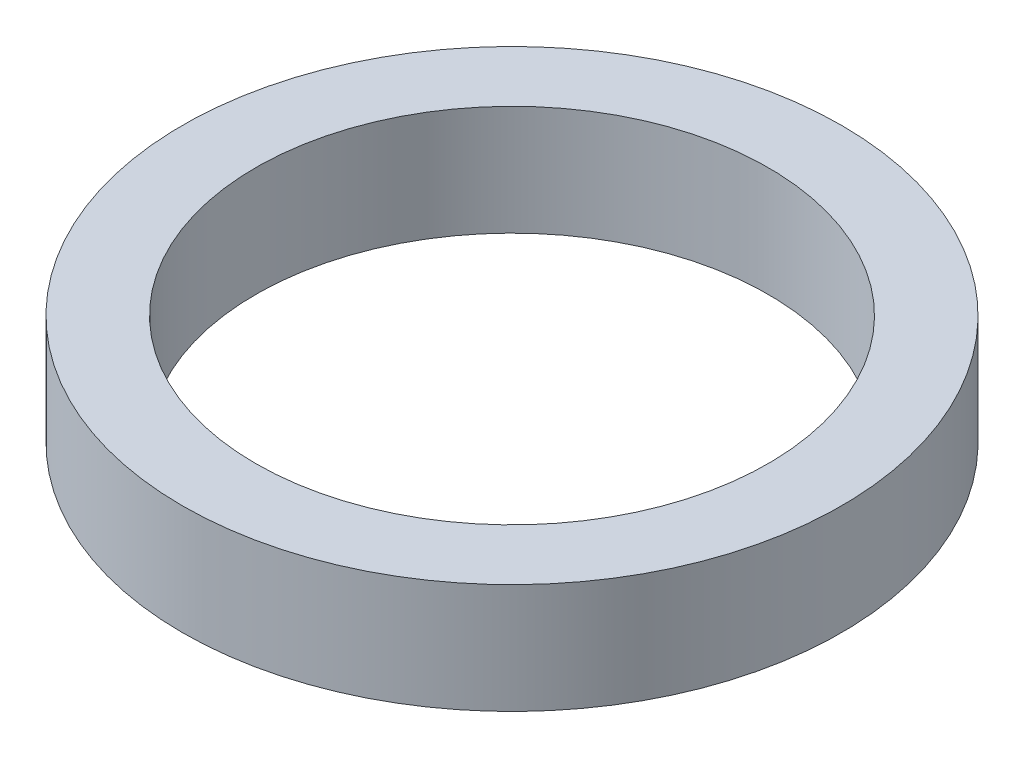
SolidWorks part; units mm, degrees
ref_plane "Front Plane" through (0, 0, 0) normal (0, 0, 1) x (1, 0, 0)
ref_plane "Top Plane" through (0, 0, 0) normal (0, 1, 0) x (1, 0, 0)
ref_plane "Right Plane" through (0, 0, 0) normal (1, 0, 0) x (0, 0, -1)
sketch "Sketch1" plane through (0, 0, 0) normal (0, 1, 0) x (1, 0, 0)
  circle A0 centre (0, 0) radius 3.5
  circle A1 centre (0, 0) radius 4.5
  dimension "D1" = 7
  dimension "D2" = 9
extrude "Boss-Extrude1" add sketch "Sketch1" along normal blind 1.5
